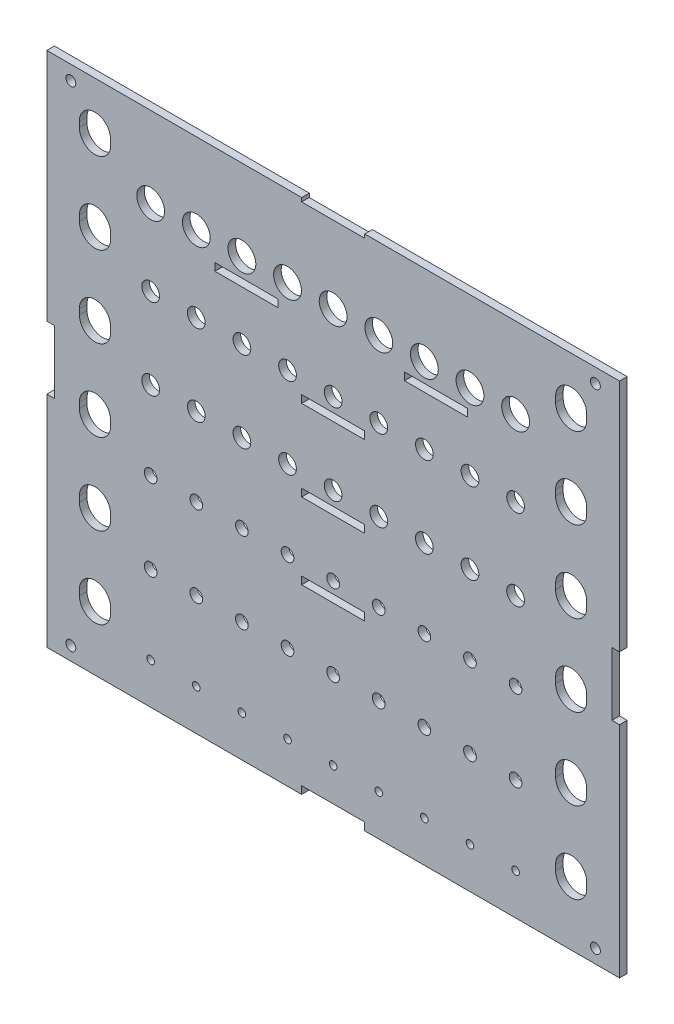
SolidWorks part; units mm, degrees
ref_plane "Спереди" through (0, 0, 0) normal (0, 0, 1) x (1, 0, 0)
ref_plane "Сверху" through (0, 0, 0) normal (0, 1, 0) x (1, 0, 0)
ref_plane "Справа" through (0, 0, 0) normal (1, 0, 0) x (0, 0, -1)
sketch "Эскиз1" plane through (0, 0, 0) normal (0, 0, 1) x (1, 0, 0)
  line L0 (98.1233, 112.3283) -> (98.1233, -117.6717)
  line L1 (-131.8767, 112.3283) -> (98.1233, 112.3283)
  line L2 (-131.8767, 112.3283) -> (-131.8767, -117.6717)
  line L3 (-131.8767, -117.6717) -> (98.1233, -117.6717)
  line L5 (-110.8767, 81.5686) -> (-110.8767, 79.3686) construction
  line L6 (77.0233, 81.5686) -> (77.0233, 79.3686) construction
  line L7 (83.1733, 81.5686) -> (83.1733, 79.3686)
  line L8 (70.8733, 81.5686) -> (70.8733, 79.3686)
  line L9 (-104.7267, 81.5686) -> (-104.7267, 79.3686)
  line L10 (83.1733, 49.5686) -> (83.1733, 47.3686)
  line L11 (70.8733, 49.5686) -> (70.8733, 47.3686)
  line L12 (-110.8767, 49.5686) -> (-110.8767, 47.3686) construction
  line L13 (-104.7267, 49.5686) -> (-104.7267, 47.3686)
  line L14 (-117.0267, 49.5686) -> (-117.0267, 47.3686)
  line L15 (77.0233, 49.5686) -> (77.0233, 47.3686) construction
  line L16 (83.1733, 17.5686) -> (83.1733, 15.3686)
  line L17 (70.8733, 17.5686) -> (70.8733, 15.3686)
  line L18 (-110.8767, 17.5686) -> (-110.8767, 15.3686) construction
  line L19 (-104.7267, 17.5686) -> (-104.7267, 15.3686)
  line L20 (-117.0267, 17.5686) -> (-117.0267, 15.3686)
  line L21 (77.0233, 17.5686) -> (77.0233, 15.3686) construction
  line L22 (83.1733, -14.4314) -> (83.1733, -16.6314)
  line L23 (70.8733, -14.4314) -> (70.8733, -16.6314)
  line L24 (-110.8767, -14.4314) -> (-110.8767, -16.6314) construction
  line L25 (-104.7267, -14.4314) -> (-104.7267, -16.6314)
  line L26 (-117.0267, -14.4314) -> (-117.0267, -16.6314)
  line L27 (77.0233, -14.4314) -> (77.0233, -16.6314) construction
  line L28 (83.1733, -46.4314) -> (83.1733, -48.6314)
  line L29 (70.8733, -46.4314) -> (70.8733, -48.6314)
  line L30 (-110.8767, -46.4314) -> (-110.8767, -48.6314) construction
  line L31 (-104.7267, -46.4314) -> (-104.7267, -48.6314)
  line L32 (-117.0267, 81.5686) -> (-117.0267, 79.3686)
  line L33 (-117.0267, -46.4314) -> (-117.0267, -48.6314)
  line L34 (77.0233, -46.4314) -> (77.0233, -48.6314) construction
  line L35 (83.1733, -78.4314) -> (83.1733, -80.6314)
  line L36 (70.8733, -78.4314) -> (70.8733, -80.6314)
  line L37 (-110.8767, -78.4314) -> (-110.8767, -80.6314) construction
  line L38 (-104.7267, -78.4314) -> (-104.7267, -80.6314)
  line L39 (-117.0267, -78.4314) -> (-117.0267, -80.6314)
  line L40 (77.0233, -78.4314) -> (77.0233, -80.6314) construction
  line L41 (-110.8767, 73.2186) -> (77.0233, 73.2186) construction
  line L42 (77.0233, 41.2186) -> (-110.8767, 41.2186) construction
  line L43 (-1110.8767, 9.2186) -> (48889.1233, 9.2186) construction
  line L44 (-922.9767, -22.7814) -> (49077.0233, -22.7814) construction
  line L45 (-922.9767, -86.7814) -> (49077.0233, -86.7814) construction
  line L46 (-110.8767, -54.7814) -> (77.0233, -54.7814) construction
  circle A2 centre (-120.4036, 93.6886) radius 1.95
  circle A3 centre (86.5964, 93.6886) radius 1.95
  circle A4 centre (86.5964, -99.3114) radius 1.95
  circle A5 centre (-120.4036, -99.3114) radius 1.95
  circle A71 centre (-88.9036, 67.4886) radius 5.4897
  circle A73 centre (-88.9036, 5.4886) radius 3.5
  circle A75 centre (-88.9036, -57.5114) radius 2.5
  circle A76 centre (-88.9036, -88.5114) radius 1.5
  arc A117 (83.1733, 81.5686) -> (70.8733, 81.5686) centre (77.0233, 81.5686) ccw
  arc A118 (70.8733, 79.3686) -> (83.1733, 79.3686) centre (77.0233, 79.3686) ccw
  arc A119 (70.8733, 47.3686) -> (83.1733, 47.3686) centre (77.0233, 47.3686) ccw
  arc A120 (83.1733, 49.5686) -> (70.8733, 49.5686) centre (77.0233, 49.5686) ccw
  arc A121 (-104.7267, 49.5686) -> (-117.0267, 49.5686) centre (-110.8767, 49.5686) ccw
  arc A122 (-117.0267, 47.3686) -> (-104.7267, 47.3686) centre (-110.8767, 47.3686) ccw
  arc A123 (70.8733, 15.3686) -> (83.1733, 15.3686) centre (77.0233, 15.3686) ccw
  arc A124 (83.1733, 17.5686) -> (70.8733, 17.5686) centre (77.0233, 17.5686) ccw
  arc A125 (-104.7267, 17.5686) -> (-117.0267, 17.5686) centre (-110.8767, 17.5686) ccw
  arc A126 (-117.0267, 15.3686) -> (-104.7267, 15.3686) centre (-110.8767, 15.3686) ccw
  arc A127 (70.8733, -16.6314) -> (83.1733, -16.6314) centre (77.0233, -16.6314) ccw
  arc A128 (83.1733, -14.4314) -> (70.8733, -14.4314) centre (77.0233, -14.4314) ccw
  arc A129 (-104.7267, -14.4314) -> (-117.0267, -14.4314) centre (-110.8767, -14.4314) ccw
  arc A130 (-117.0267, -16.6314) -> (-104.7267, -16.6314) centre (-110.8767, -16.6314) ccw
  arc A131 (70.8733, -48.6314) -> (83.1733, -48.6314) centre (77.0233, -48.6314) ccw
  arc A132 (83.1733, -46.4314) -> (70.8733, -46.4314) centre (77.0233, -46.4314) ccw
  arc A133 (-104.7267, -46.4314) -> (-117.0267, -46.4314) centre (-110.8767, -46.4314) ccw
  arc A134 (-117.0267, -48.6314) -> (-104.7267, -48.6314) centre (-110.8767, -48.6314) ccw
  arc A135 (70.8733, -80.6314) -> (83.1733, -80.6314) centre (77.0233, -80.6314) ccw
  arc A136 (83.1733, -78.4314) -> (70.8733, -78.4314) centre (77.0233, -78.4314) ccw
  arc A137 (-104.7267, -78.4314) -> (-117.0267, -78.4314) centre (-110.8767, -78.4314) ccw
  arc A138 (-117.0267, -80.6314) -> (-104.7267, -80.6314) centre (-110.8767, -80.6314) ccw
  arc A139 (-104.7267, 81.5686) -> (-117.0267, 81.5686) centre (-110.8767, 81.5686) ccw
  arc A140 (-117.0267, 79.3686) -> (-104.7267, 79.3686) centre (-110.8767, 79.3686) ccw
  circle A141 centre (-88.9036, 37.4886) radius 3.5
  circle A142 centre (-88.9036, -25.5114) radius 2.5
  circle A143 centre (-70.9036, 67.4886) radius 5.4897
  circle A144 centre (-70.9036, 5.4886) radius 3.5
  circle A145 centre (-70.9036, -57.5114) radius 2.5
  circle A146 centre (-70.9036, -88.5114) radius 1.5
  circle A147 centre (-70.9036, 37.4886) radius 3.5
  circle A148 centre (-70.9036, -25.5114) radius 2.5
  circle A149 centre (-52.9036, 67.4886) radius 5.4897
  circle A150 centre (-52.9036, 5.4886) radius 3.5
  circle A151 centre (-52.9036, -57.5114) radius 2.5
  circle A152 centre (-52.9036, -88.5114) radius 1.5
  circle A153 centre (-52.9036, 37.4886) radius 3.5
  circle A154 centre (-52.9036, -25.5114) radius 2.5
  circle A155 centre (-34.9036, 67.4886) radius 5.4897
  circle A156 centre (-34.9036, 5.4886) radius 3.5
  circle A157 centre (-34.9036, -57.5114) radius 2.5
  circle A158 centre (-34.9036, -88.5114) radius 1.5
  circle A159 centre (-34.9036, 37.4886) radius 3.5
  circle A160 centre (-34.9036, -25.5114) radius 2.5
  circle A161 centre (-16.9036, 67.4886) radius 5.4897
  circle A162 centre (-16.9036, 5.4886) radius 3.5
  circle A163 centre (-16.9036, -57.5114) radius 2.5
  circle A164 centre (-16.9036, -88.5114) radius 1.5
  circle A165 centre (-16.9036, 37.4886) radius 3.5
  circle A166 centre (-16.9036, -25.5114) radius 2.5
  circle A167 centre (1.0964, 67.4886) radius 5.4897
  circle A168 centre (1.0964, 5.4886) radius 3.5
  circle A169 centre (1.0964, -57.5114) radius 2.5
  circle A170 centre (1.0964, -88.5114) radius 1.5
  circle A171 centre (1.0964, 37.4886) radius 3.5
  circle A172 centre (1.0964, -25.5114) radius 2.5
  circle A173 centre (19.0964, 67.4886) radius 5.4897
  circle A174 centre (19.0964, 5.4886) radius 3.5
  circle A175 centre (19.0964, -57.5114) radius 2.5
  circle A176 centre (19.0964, -88.5114) radius 1.5
  circle A177 centre (19.0964, 37.4886) radius 3.5
  circle A178 centre (19.0964, -25.5114) radius 2.5
  circle A179 centre (37.0964, 67.4886) radius 5.4897
  circle A180 centre (37.0964, 5.4886) radius 3.5
  circle A181 centre (37.0964, -57.5114) radius 2.5
  circle A182 centre (37.0964, -88.5114) radius 1.5
  circle A183 centre (37.0964, 37.4886) radius 3.5
  circle A184 centre (37.0964, -25.5114) radius 2.5
  circle A185 centre (55.0964, 67.4886) radius 5.4897
  circle A186 centre (55.0964, 5.4886) radius 3.5
  circle A187 centre (55.0964, -57.5114) radius 2.5
  circle A188 centre (55.0964, -88.5114) radius 1.5
  circle A189 centre (55.0964, 37.4886) radius 3.5
  circle A190 centre (55.0964, -25.5114) radius 2.5
  point P7 (-110.8767, 80.4686)
  point P28 (77.0233, 80.4686)
  point P45 (-110.8767, 48.4686)
  point P49 (77.0233, 48.4686)
  point P53 (-110.8767, 79.3686)
  point P60 (-110.8767, 16.4686)
  point P64 (77.0233, 16.4686)
  point P122 (-110.8767, -15.5314)
  point P126 (77.0233, -15.5314)
  point P136 (-110.8767, -47.5314)
  point P140 (77.0233, -47.5314)
  point P150 (-110.8767, -79.5314)
  point P154 (77.0233, -79.5314)
  point P217 (-110.8767, 9.2186)
  point P220 (77.0233, -22.7814)
  dimension "D5" = 6
  dimension "D9" = 6.15
  dimension "D6" = 3.9
  dimension "D7" = 3.9
  dimension "D8" = 3.9
  dimension "D11" = 3.9
  dimension "D15" = 0.23
  dimension "D14" = 3
  dimension "D20" = 5
  dimension "D21" = 5
  dimension "D22" = 10.9794
  dimension "D30" = 42.9731
  dimension "D1" = 230
  dimension "D2" = 230
  dimension "D13" = 21
  dimension "D4" = 9
  dimension "D10" = 2.2
  dimension "D12" = 0.2403
  dimension "D16" = 0.23
  dimension "D17" = 0.23
  dimension "D18" = 0.23
  dimension "D19" = 0.23
  dimension "D25" = 40.4731
  dimension "D26" = 41.4731
  dimension "D27" = 42.9731
  dimension "D28" = 43.0269
  dimension "D29" = 43.0269
  dimension "D3" = 2
extrude "Бобышка-Вытянуть1" add sketch "Эскиз1" along normal blind 3
sketch "Эскиз2" plane through (0, 0, 3) normal (0, 0, 1) x (1, 0, 0)
  line L0 (98.1233, -117.6717) -> (98.1233, 112.3283) construction
  line L1 (-131.8767, 112.3283) -> (98.1233, 112.3283)
  line L2 (-131.8767, 112.3283) -> (-131.8767, 99.1886)
  line L3 (-129.8767, 99.3283) -> (96.1233, 99.3283)
  line L4 (98.1233, 112.3283) -> (98.1233, 99.1886)
  line L5 (-63.5767, 56.9989) -> (-38.7267, 56.9989)
  line L6 (-131.8767, -117.6717) -> (98.1233, -117.6717)
  line L7 (-131.8767, -117.6717) -> (-131.8767, -104.8114)
  line L8 (-129.8767, -104.6717) -> (96.1233, -104.6717)
  line L9 (98.1233, -117.6717) -> (98.1233, -104.8114)
  line L10 (-131.8767, 112.3283) -> (-124.9036, 112.3283)
  line L11 (-131.8767, 112.3283) -> (-131.8767, -117.6717)
  line L12 (-131.8767, -117.6717) -> (-124.9036, -117.6717)
  line L13 (-129.8767, 99.3283) -> (-129.8767, -104.6717)
  line L14 (98.1233, -117.6717) -> (91.0964, -117.6717)
  line L15 (98.1233, -117.6717) -> (98.1233, 112.3283)
  line L16 (98.1233, 112.3283) -> (91.0964, 112.3283)
  line L17 (96.1233, -104.6717) -> (96.1233, 99.3283)
  line L18 (11.2733, 59.9989) -> (36.1233, 59.9989)
  line L19 (11.2733, 59.9989) -> (11.2733, 56.9989)
  line L20 (11.2733, 56.9989) -> (36.1233, 56.9989)
  line L21 (36.1233, 59.9989) -> (36.1233, 56.9989)
  line L22 (-29.3267, 31.9886) -> (-4.4267, 31.9886)
  line L23 (-29.3267, 31.9886) -> (-29.3267, 28.9886)
  line L24 (-29.3267, 28.9886) -> (-4.4267, 28.9886)
  line L25 (-4.4267, 31.9886) -> (-4.4267, 28.9886)
  line L26 (-29.3267, -0.0114) -> (-4.4267, -0.0114)
  line L27 (-29.3267, -0.0114) -> (-29.3267, -3.0114)
  line L28 (-29.3267, -3.0114) -> (-4.4267, -3.0114)
  line L29 (-4.4267, -0.0114) -> (-4.4267, -3.0114)
  line L30 (-29.3267, -30.0114) -> (-4.4267, -30.0114)
  line L31 (-29.3267, -30.0114) -> (-29.3267, -33.0114)
  line L32 (-29.3267, -33.0114) -> (-4.4267, -33.0114)
  line L33 (-4.4267, -30.0114) -> (-4.4267, -33.0114)
  line L34 (-29.3267, -104.6717) -> (-4.4267, -104.6717)
  line L35 (-29.3267, -104.6717) -> (-29.3267, -101.6717)
  line L36 (-29.3267, -101.6717) -> (-4.4267, -101.6717)
  line L37 (-4.4267, -104.6717) -> (-4.4267, -101.6717)
  line L38 (-129.8767, 6.7783) -> (-126.8767, 6.7783)
  line L39 (-129.8767, 6.7783) -> (-129.8767, -18.1217)
  line L40 (-129.8767, -18.1217) -> (-126.8767, -18.1217)
  line L41 (-126.8767, 6.7783) -> (-126.8767, -18.1217)
  line L42 (96.1233, 6.7783) -> (93.1233, 6.7783)
  line L43 (96.1233, 6.7783) -> (96.1233, -18.1217)
  line L44 (96.1233, -18.1217) -> (93.1233, -18.1217)
  line L45 (93.1233, 6.7783) -> (93.1233, -18.1217)
  line L46 (-29.3267, 99.3283) -> (-4.4267, 99.3283)
  line L47 (-29.3267, 99.3283) -> (-29.3267, 97.8283)
  line L48 (-29.3267, 97.8283) -> (-4.4267, 97.8283)
  line L49 (-4.4267, 99.3283) -> (-4.4267, 97.8283)
  line L50 (-63.5767, 56.9989) -> (-63.5767, 59.9989)
  line L51 (-63.5767, 59.9989) -> (-38.7267, 59.9989)
  line L52 (-38.7267, 56.9989) -> (-38.7267, 59.9989)
  line L53 (-94.2809, -932.5114) -> (-94.2809, 49067.4886) construction
  line L54 (60.4737, -932.5114) -> (60.4737, 49067.4886) construction
  circle A0 centre (-16.9036, 67.4886) radius 5.4897 construction
  circle A1 centre (-88.9036, 67.4886) radius 5.4897 construction
  circle A2 centre (-16.9036, 37.4886) radius 3.5 construction
  circle A3 centre (55.0964, 67.4886) radius 5.4897 construction
  circle A5 centre (-16.9036, 5.4886) radius 3.5 construction
  circle A7 centre (-16.9036, -25.5114) radius 2.5 construction
  dimension "D7" = 2
  dimension "D38" = 24.85
  dimension "D40" = 2
  dimension "D42" = 40.9731
  dimension "D43" = 41.0269
  dimension "D1" = 13
  dimension "D2" = 2
  dimension "D3" = 2
  dimension "D4" = 13
  dimension "D5" = 3
  dimension "D6" = 24.85
  dimension "D8" = 3
  dimension "D9" = 3
  dimension "D10" = 3
  dimension "D11" = 24.9
  dimension "D12" = 24.9
  dimension "D13" = 24.9
  dimension "D14" = 2
  dimension "D15" = 2
  dimension "D16" = 2
  dimension "D17" = 24.9
  dimension "D18" = 1.5
  dimension "D19" = 226
  dimension "D20" = 3
  dimension "D21" = 3
  dimension "D22" = 24.9
  dimension "D23" = 24.9
  dimension "D24" = 3
  dimension "D25" = 24.9
  dimension "D26" = 100.55
  dimension "D27" = 100.55
  dimension "D28" = 92.55
  dimension "D29" = 92.55
  dimension "D30" = 60
  dimension "D31" = 39.3294
  dimension "D32" = 67.3397
  dimension "D33" = 100.55
  dimension "D34" = 100.55
  dimension "D35" = 99.3397
  dimension "D36" = 129.3397
  dimension "D37" = 100.55
  dimension "D39" = 3
  dimension "D41" = 50
extrude "Вырез-Вытянуть1" cut sketch "Эскиз2" against normal blind 10 contours L9 L15 L4 L1 L2 L11 L7 L6 L17 L8 L13 L3 | L21 L18 L19 L20 | L29 L26 L27 L28 | L41 L38 L13 L40 | L5 L52 L51 L50 | L48 L49 L46 L47 | L22 L25 L24 L23 | L30 L33 L32 L31 | L45 L44 L43 L42 | L36 L37 L34 L35
